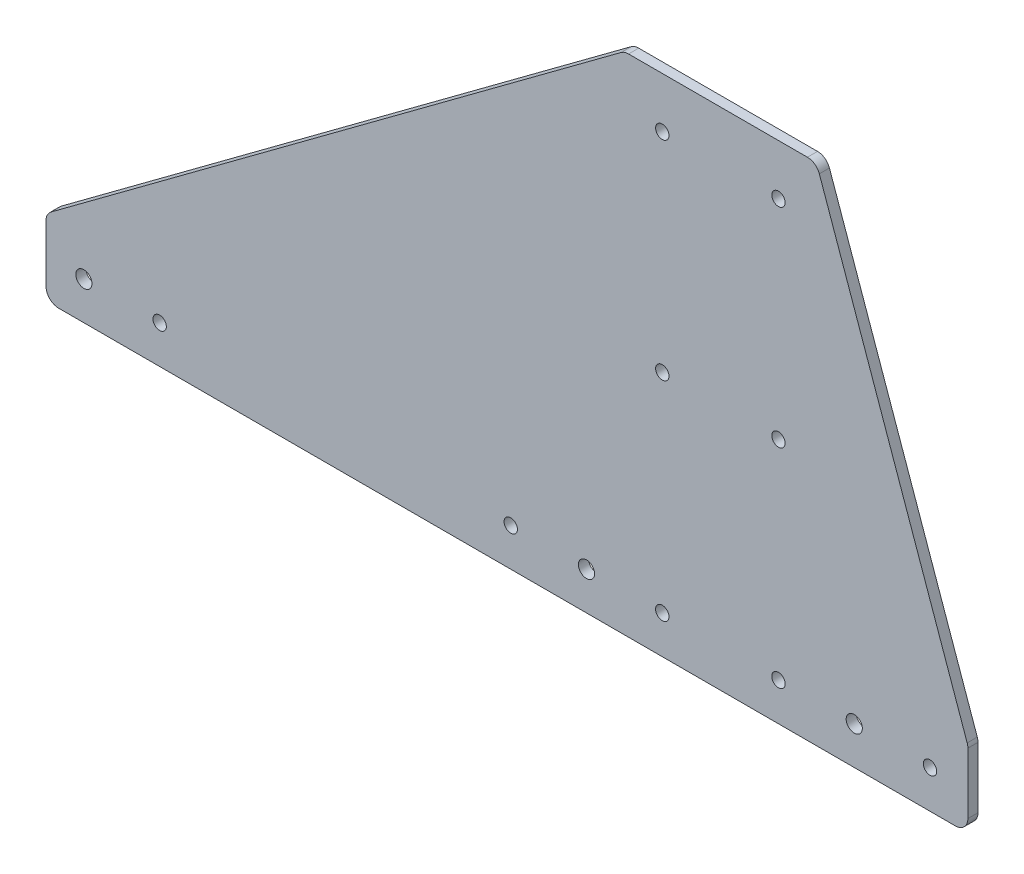
SolidWorks part; units mm, degrees
ref_plane "Front Plane" through (0, 0, 0) normal (0, 0, 1) x (1, 0, 0)
ref_plane "Top Plane" through (0, 0, 0) normal (0, 1, 0) x (1, 0, 0)
ref_plane "Right Plane" through (0, 0, 0) normal (1, 0, 0) x (0, 0, -1)
sketch "Sketch1" plane through (0, 0, 0) normal (0, 0, 1) x (1, 0, 0)
  line L0 (-267, -30) -> (98, -30)
  line L1 (98, -30) -> (98, 0)
  line L2 (98, 0) -> (38, 170)
  line L3 (38, 170) -> (-38, 170)
  line L4 (-38, 170) -> (-267, 0)
  line L5 (-267, 0) -> (-267, -30)
  line L6 (4.4, 0) -> (-4.4, 0) construction
  line L7 (0, -4.4) -> (0, 4.4) construction
  dimension "D1" = 30
  dimension "D2" = 365
  dimension "D3" = 30
  dimension "D4" = 98
  dimension "D5" = 200
  dimension "D6" = 60
  dimension "D7" = 76
  dimension "D8" = 30
extrude "Boss-Extrude1" add sketch "Sketch1" along normal blind 4
hole_wizard "M5 Clearance Hole1" positions "Sketch4" profile "Sketch3" hole size "M5" standard "ISO" end condition through all
sketch "Sketch4" plane through (0, 0, 4) normal (0, 0, 1) x (1, 0, 0)
  line L0 (0, 0) -> (0, 82.324) construction
  line L1 (0, -55) -> (0, 55) construction
  line L2 (-267, -30) -> (98, -30) construction
  line L4 (-23, -15) -> (-23, 150)
  line L6 (55, 0) -> (-55, 0) construction
  line L7 (-267, 0) -> (-267, -30) construction
  point P0 (-23, 150)
  point P2 (-23, 67.5)
  point P3 (-23, -15)
  point P17 (23, -15)
  point P18 (23, 150)
  point P19 (23, 67.5)
  point P28 (-83, -15)
  point P36 (83, -15)
  point P38 (-222, -15)
  dimension "D1" = 180
  dimension "D2" = 15
  dimension "D3" = 23
  dimension "D4" = 83
  dimension "D5" = 15
  dimension "D6" = 15
  dimension "D7" = 45
sketch "Sketch3" plane through (-23, 150, 4) normal (1, 0, 0) x (0, -1, 0)
  line L0 (0, 0) -> (0, 4)
  line L1 (0, 4) -> (2.65, 4)
  line L2 (2.65, 4) -> (2.65, 0)
  line L5 (2.65, 0) -> (0, 0)
  line L11 (0, -6.35) -> (0, 107.95) construction
  dimension "Thru Hole Dia." = 5.3
  dimension "Thru Hole Depth" = 4
fillet "Fillet1" radius 5 6 edges at (38, 170, 2) (98, 0, 2) (98, -30, 2) (-267, -30, 2) (-267, 0, 2) (-38, 170, 2)
hole_wizard "M6 Clearance Hole1" positions "Sketch6" profile "Sketch5" hole size "M6" standard "ISO"
sketch "Sketch6" plane through (0, 0, 4) normal (0, 0, 1) x (1, 0, 0)
  line L0 (55, 0) -> (-55, 0) construction
  line L1 (-252, -15) -> (53, -15) construction
  line L3 (-267, -2.5154) -> (-267, -25) construction
  line L4 (0, -55) -> (0, 55) construction
  point P0 (-252, -15)
  point P3 (-53, -15)
  point P6 (53, -15)
  dimension "D1" = 15
  dimension "D2" = 15
  dimension "D3" = 53
  dimension "D4" = 53
  dimension "D5" = 15
sketch "Sketch5" plane through (-252, -15, 4) normal (1, 0, 0) x (0, -1, 0)
  line L0 (0, 0) -> (0, 9.9228)
  line L1 (0, 9.9228) -> (3.2, 8)
  line L2 (3.2, 8) -> (3.2, 0)
  line L5 (3.2, 0) -> (0, 0)
  line L10 (0, 9.9228) -> (-3.2, 8) construction
  line L11 (0, -6.35) -> (0, 107.95) construction
  dimension "Hole Dia." = 6.4
  dimension "Hole Depth" = 8
  dimension "Drill Angle" = 118
